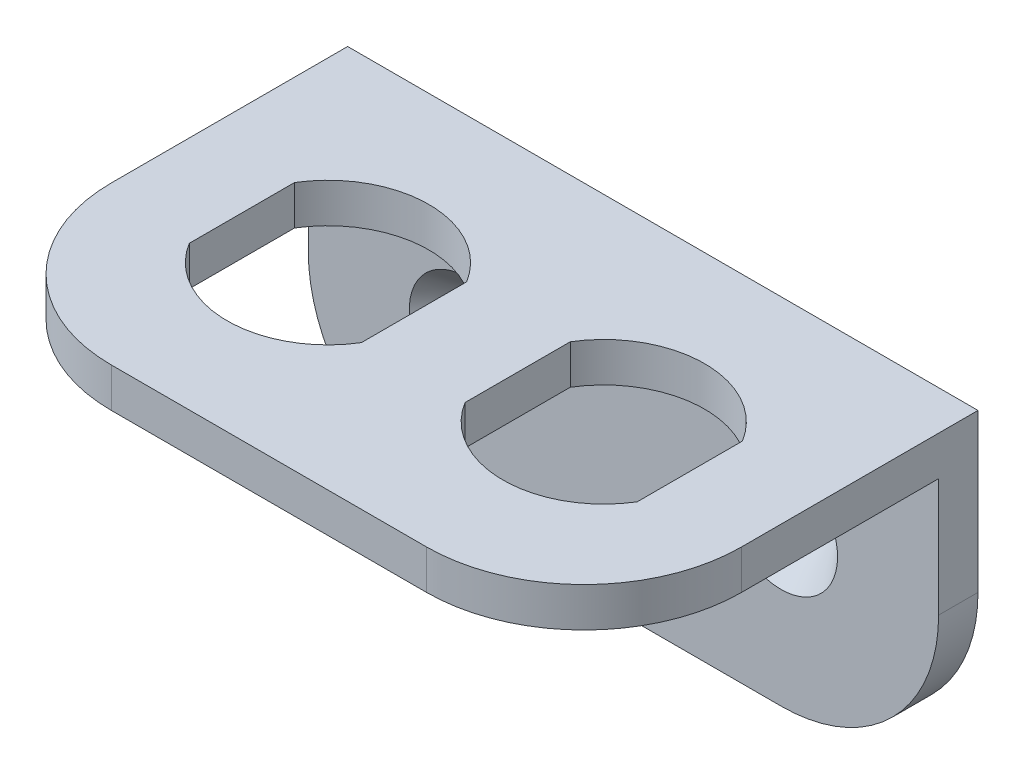
SolidWorks part; units mm, degrees
material "6061-T6 (SS)"
ref_plane "Front Plane" through (0, 0, 0) normal (0, 0, 1) x (1, 0, 0)
ref_plane "Top Plane" through (0, 0, 0) normal (0, 1, 0) x (1, 0, 0)
ref_plane "Right Plane" through (0, 0, 0) normal (1, 0, 0) x (0, 0, -1)
sketch "Sketch1" plane through (0, 0, 0) normal (1, 0, 0) x (0, 0, -1)
  line L0 (0, 0) -> (-31.75, 0)
  line L1 (-31.75, 0) -> (-31.75, -3.175)
  line L2 (-31.75, -3.175) -> (-3.175, -3.175)
  line L3 (-3.175, -3.175) -> (-3.175, -25.4)
  line L4 (-3.175, -25.4) -> (0, -25.4)
  line L5 (0, -25.4) -> (0, 0)
  dimension "D1" = 31.75
  dimension "D2" = 25.4
  dimension "D3" = 3.175
  dimension "D4" = 3.175
extrude "Boss-Extrude1" add sketch "Sketch1" along normal blind 50.8
sketch "Sketch2" plane through (0, 0, 0) normal (0, 1, 0) x (1, 0, 0)
  line L0 (0, -15.875) -> (50.8, -15.875) construction
  line L3 (25.4, 0) -> (25.4, -31.75) construction
  line L4 (50.8, 0) -> (0, 0) construction
  line L5 (50.8, -31.75) -> (0, -31.75) construction
  line L6 (7.3533, -11.6346) -> (7.3533, -20.1154)
  line L7 (21.2217, -11.6346) -> (21.2217, -20.1154)
  line L8 (29.5783, -11.6346) -> (29.5783, -20.1154)
  line L9 (43.4467, -11.6346) -> (43.4467, -20.1154)
  line L10 (0, 0) -> (0, -31.75) construction
  arc A0 (7.3533, -20.1154) -> (21.2217, -20.1154) centre (14.2875, -15.875) ccw
  arc A1 (29.5783, -20.1154) -> (43.4467, -20.1154) centre (36.5125, -15.875) ccw
  arc A2 (21.2217, -11.6346) -> (7.3533, -11.6346) centre (14.2875, -15.875) ccw
  arc A3 (43.4467, -11.6346) -> (29.5783, -11.6346) centre (36.5125, -15.875) ccw
  circle A4 centre (14.2875, -15.875) radius 10.541 construction
  point P4 (0, -15.875)
  dimension "D3" = 16.256
  dimension "D8" = 8.128
  dimension "D9" = 21.082
  dimension "D1" = 22.225
  dimension "D2" = 11.1125
  dimension "D4" = 13.8684
  dimension "D5" = 6.9342
  dimension "D6" = 13.8684
  dimension "D7" = 6.9342
extrude "Cut-Extrude1" cut sketch "Sketch2" against normal through all
fillet "Fillet1" radius 12.7 4 edges at (0, -25.4, 1.5875) (50.8, -25.4, 1.5875) (50.8, -1.5875, 31.75) (0, -1.5875, 31.75)
sketch "Sketch3" plane through (0, 0, 3.175) normal (0, 0, 1) x (1, 0, 0)
  line L0 (0, -12.7) -> (50.8, -12.7) construction
hole_wizard "CSK for #8 Flat Head Socket Cap Screw1" positions "Sketch5" profile "Sketch4" countersink size "#8" standard "Ansi Inch" end condition up to next
sketch "Sketch5" plane through (0, 0, 3.175) normal (0, 0, 1) x (1, 0, 0)
  line L0 (0, -12.7) -> (50.8, -12.7) construction
  point P0 (12.7, -12.7)
  point P1 (38.1, -12.7)
  point P7 (25.4, -12.7)
  dimension "D1" = 25.4
  dimension "D2" = 12.7
sketch "Sketch4" plane through (12.7, -12.7, 3.175) normal (1, 0, 0) x (0, -1, 0)
  line L0 (0, 0) -> (0, 3.175)
  line L1 (0, 3.175) -> (2.2479, 3.175)
  line L2 (2.2479, 3.175) -> (2.2479, 2.659)
  line L3 (2.2479, 2.659) -> (4.5593, 0)
  line L5 (4.5593, 0) -> (0, 0)
  line L6 (-2.2479, 2.659) -> (-4.5593, 0) construction
  line L11 (0, -6.35) -> (0, 107.95) construction
  dimension "Thru Hole Dia." = 4.4958
  dimension "Thru Hole Depth" = 3.175
  dimension "Near C'Sink Dia." = 9.1186
  dimension "Near C'Sink Angle" = 82
